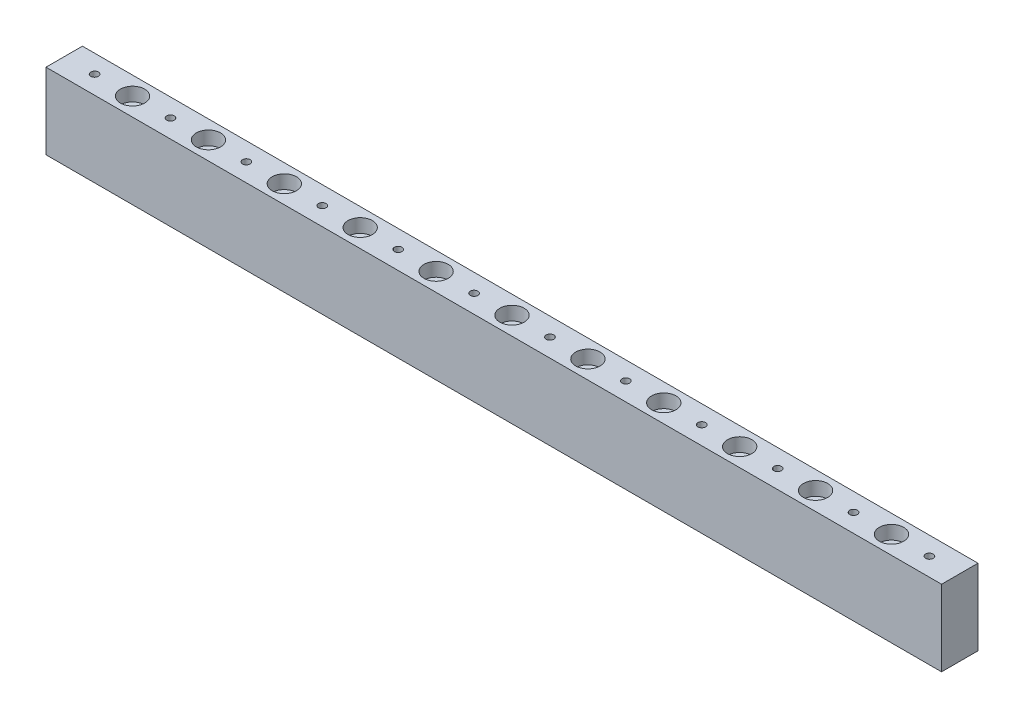
SolidWorks part; units mm, degrees
ref_plane "前视" through (0, 0, 0) normal (0, 0, 1) x (1, 0, 0)
ref_plane "上视" through (0, 0, 0) normal (0, 1, 0) x (1, 0, 0)
ref_plane "右视" through (0, 0, 0) normal (1, 0, 0) x (0, 0, -1)
sketch "草图2" plane through (0, 0, 0) normal (0, 1, 0) x (1, 0, 0)
  line L1 (0, 6) -> (295, 6)
  line L2 (0, 6) -> (0, -6)
  line L3 (0, -6) -> (295, -6)
  line L4 (295, 6) -> (295, -6)
  dimension "D1" = 12
  dimension "D2" = 6
  dimension "D3" = 295
extrude "拉伸1" add sketch "草图2" along normal blind 25
sketch "草图3" plane through (0, 25, 0) normal (0, 1, 0) x (1, 0, 0)
  point P0 (10, 0)
  dimension "D1" = 10
hole_wizard "M3 螺纹孔1" positions "3D草图1" profile "草图4" tap size "M3" standard "ISO"
sketch3d "3D草图1"
  point P0 (10, 25, 0)
sketch "草图4" plane through (10, 25, 0) normal (1, 0, 0) x (0, 0, 1)
  line L0 (0, 0) -> (0, 8.2511)
  line L1 (0, 8.2511) -> (1.25, 7.5)
  line L2 (1.25, 7.5) -> (1.25, 0)
  line L5 (1.25, 0) -> (0, 0)
  line L10 (0, 8.2511) -> (-1.25, 7.5) construction
  line L11 (0, -6.35) -> (0, 107.95) construction
  dimension "螺纹孔钻头直径" = 2.5
  dimension "螺纹孔钻头深度" = 7.5
  dimension "导头角度" = 118
cosmetic thread "孔螺蚊线1" parameters "D1"=6, "D2"=3
pattern_linear "阵列(线性)1" count 12 spacing 25 along (1, 0, 0) of "M3 螺纹孔1"
sketch "草图5" plane through (0, 0, 6) normal (0, 0, 1) x (1, 0, 0)
  line L0 (147.5, 0) -> (147.5, 25) construction
  line L1 (0, 0) -> (295, 0) construction
  line L2 (0, 25) -> (295, 25) construction
  point P6 (147.5, 12.5)
sketch "草图6" plane through (295, 0, 0) normal (1, 0, 0) x (0, 0, -1)
  line L0 (-6, 25) -> (6, 25) construction
  line L1 (-3, 25) -> (6, 25)
  line L2 (-3, 25) -> (-3, 23)
  line L3 (-3, 23) -> (6, 23)
  line L4 (6, 25) -> (6, 23)
  line L5 (6, 25) -> (6, 0) construction
  line L7 (-6, 25) -> (-6, 0) construction
  dimension "D1" = 3
  dimension "D2" = 2
hole_wizard "M4 六角凹头螺钉的柱形沉头孔1" positions "草图8" profile "草图7" counterbore size "M4" standard "ISO" end condition through all
sketch "草图8" plane through (262.8463, 25, 7.8134) normal (0, 1, 0) x (-1, 0, 0)
  line L0 (254.0963, -7.8134) -> (-19.0982, -7.8134) construction
  line L3 (262.8463, -13.8134) -> (262.8463, -1.8134) construction
  circle A0 centre (252.8463, -7.8134) radius 1.25 construction
  point P0 (240.3463, -7.8134)
  dimension "D1" = 22.5
sketch "草图7" plane through (22.5, 25, 0) normal (1, 0, 0) x (0, 0, 1)
  line L0 (0, 0) -> (0, 25)
  line L1 (0, 25) -> (2.25, 25)
  line L3 (2.25, 25) -> (2.25, 4.5)
  line L4 (2.25, 4.5) -> (4, 4.5)
  line L5 (4, 4.5) -> (4, 0)
  line L7 (4, 0) -> (0, 0)
  line L11 (0, -6.35) -> (0, 107.95) construction
  dimension "通孔孔直径" = 4.5
  dimension "通孔孔深度" = 25
  dimension "柱形沉头孔直径" = 8
  dimension "柱形沉头孔深度" = 4.5
pattern_linear "阵列(线性)2" count 11 spacing 25 along (1, 0, 0) of "M4 六角凹头螺钉的柱形沉头孔1"
hole_wizard "Ø5.0 (5) 直径孔1" positions "草图10" profile "草图9" hole size "Ø5.0" standard "GB"
sketch "草图10" plane through (0, 0, 0) normal (0, -1, 0) x (-1, 0, 0)
  line L0 (-295, -6) -> (-295, 6) construction
  line L1 (0, 6) -> (0, -6) construction
  line L2 (0, 0) -> (-22.5, 0) construction
  point P0 (-11.25, 0)
  point P2 (-283.75, 0)
  dimension "D2" = 11.25
  dimension "D1" = 11.25
sketch "草图9" plane through (11.25, 0, 0) normal (1, 0, 0) x (0, 0, -1)
  line L0 (0, 0) -> (0, 8)
  line L1 (0, 8) -> (2.5, 8)
  line L2 (2.5, 8) -> (2.5, 0)
  line L5 (2.5, 0) -> (0, 0)
  line L10 (0, 8) -> (-2.5, 8) construction
  line L11 (0, -6.35) -> (0, 107.95) construction
  dimension "孔直径" = 5
  dimension "孔深度" = 8
  dimension "导头角度" = 180
